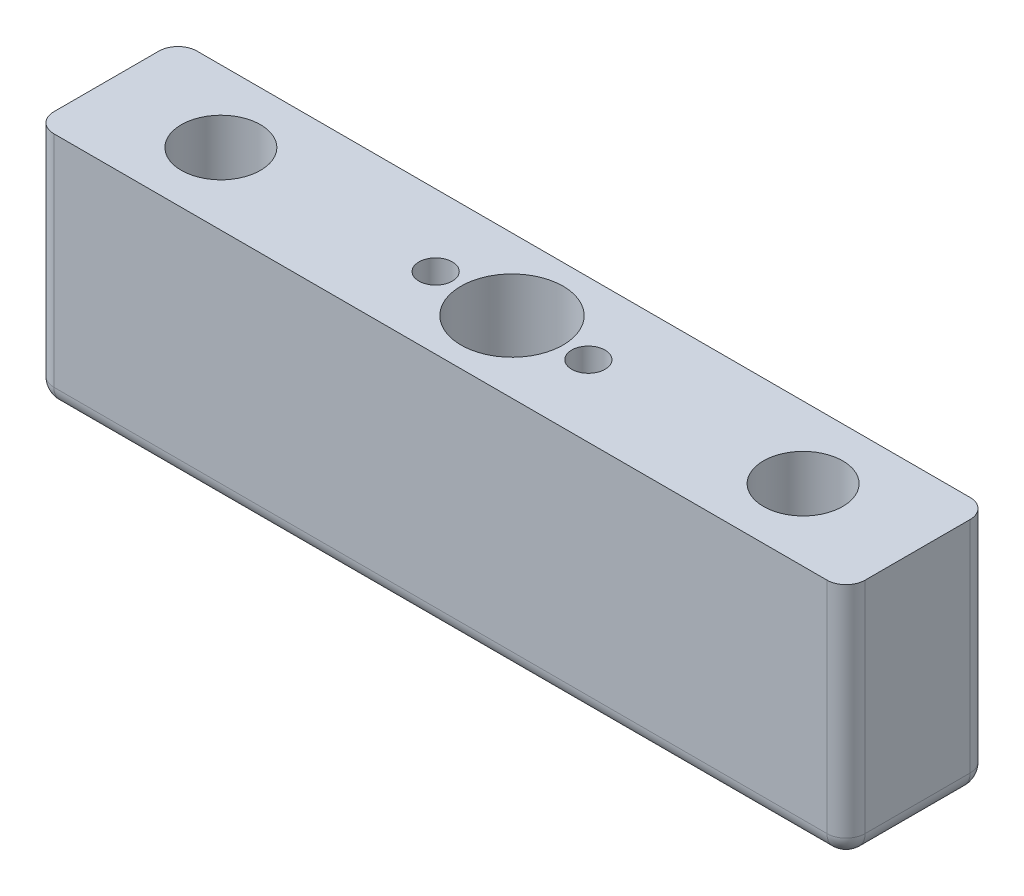
SolidWorks part; units mm, degrees
ref_plane "Alzado" through (0, 0, 0) normal (0, 0, 1) x (1, 0, 0)
ref_plane "Planta" through (0, 0, 0) normal (0, 1, 0) x (1, 0, 0)
ref_plane "Vista lateral" through (0, 0, 0) normal (1, 0, 0) x (0, 0, -1)
sketch "Croquis1" plane through (0, 0, 0) normal (0, 1, 0) x (1, 0, 0)
  line L1 (-42.5, -7.5) -> (42.5, -7.5)
  line L2 (-42.5, -7.5) -> (-42.5, 7.5)
  line L3 (-42.5, 7.5) -> (42.5, 7.5)
  line L4 (42.5, -7.5) -> (42.5, 7.5)
  line L5 (-42.5, -7.5) -> (42.5, 7.5) construction
  line L6 (-42.5, 7.5) -> (42.5, -7.5) construction
  point P0 (0, 0)
extrude "Saliente-Extruir1" add sketch "Croquis1" along normal blind 25
sketch "Croquis2" plane through (0, 0, 0) normal (0, -1, 0) x (-1, 0, 0)
  circle A0 centre (0, 0) radius 5.35
extrude "Cortar-Extruir1" cut sketch "Croquis2" against normal through all
sketch "Croquis3" plane through (0, 25, 0) normal (0, 1, 0) x (1, 0, 0)
  line L0 (42.5, 7.5) -> (42.5, 0) construction
  line L1 (42.5, -7.5) -> (42.5, 7.5) construction
  line L2 (42.5, 0) -> (30.5, 0) construction
  line L3 (-42.5, 7.5) -> (-42.5, 0) construction
  line L4 (-42.5, 7.5) -> (-42.5, -7.5) construction
  line L5 (-42.5, 0) -> (-30.5, 0) construction
  circle A0 centre (-30.5, 0) radius 4.15
  circle A1 centre (30.5, 0) radius 4.15
extrude "Cortar-Extruir2" cut sketch "Croquis3" against normal blind 18
fillet "Redondeo1" radius 2 8 edges at (42.5, 12.5, 7.5) (42.5, 12.5, -7.5) (42.5, 0, 0) (0, 0, 7.5) (-42.5, 12.5, 7.5) (0, 0, -7.5) (-42.5, 0, 0) (-42.5, 12.5, -7.5)
sketch "Croquis6" plane through (0, 25, 0) normal (0, 1, 0) x (1, 0, 0)
  line L0 (0, 0) -> (-8, 0) construction
  line L1 (-8, 0) -> (8, 0) construction
  circle A0 centre (8, 0) radius 1.75
  circle A1 centre (-8, 0) radius 1.75
extrude "Cortar-Extruir4" cut sketch "Croquis6" against normal through all contours A1 | A0
sketch "Croquis7" plane through (0, 0, 0) normal (0, -1, 0) x (1, 0, 0)
  line L5 (-22.7358, 5.5) -> (-22.7358, -5.5) construction
  line L6 (40.5, 5.5) -> (-40.5, 5.5) construction
  line L7 (-40.5, -5.5) -> (40.5, -5.5) construction
  text T0 "10" font "Century Gothic" height 7
extrude "Cortar-Extruir7" cut sketch "Croquis7" against normal blind 1
